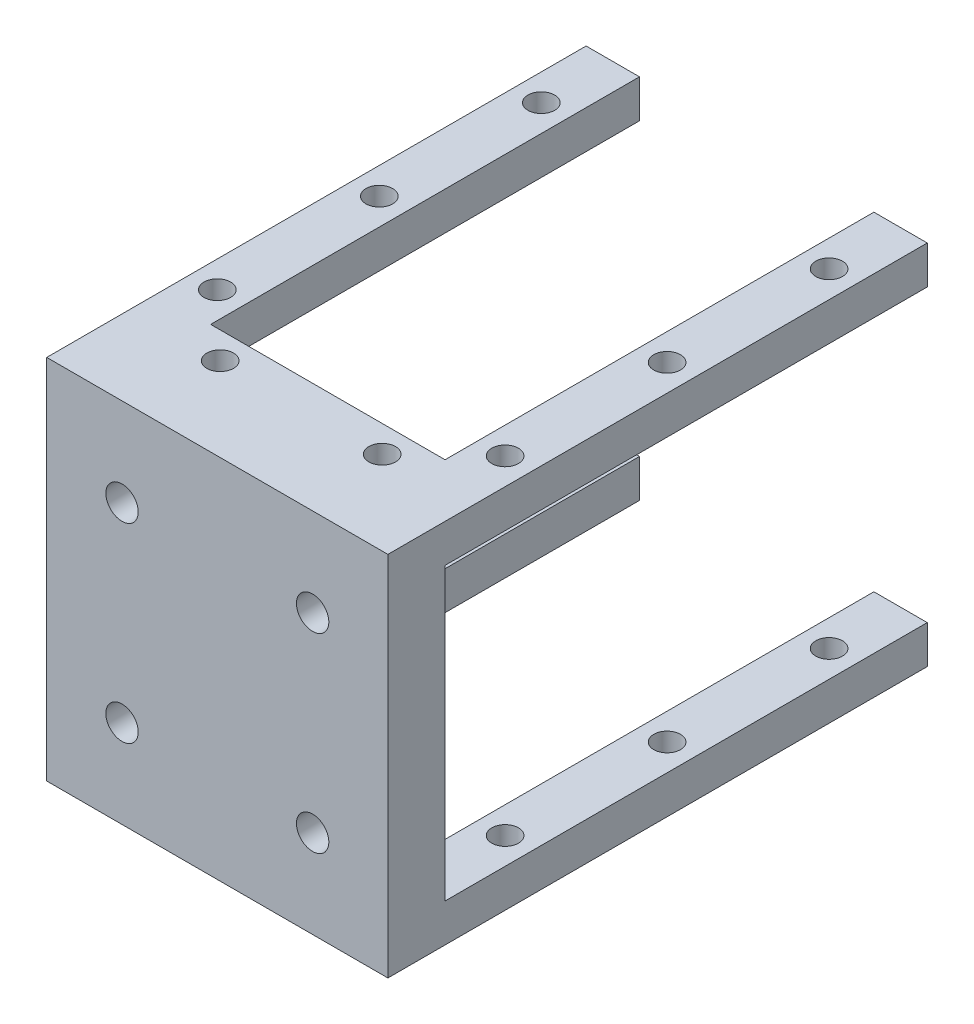
SolidWorks part; units mm, degrees
ref_plane "Front Plane" through (0, 0, 0) normal (0, 0, 1) x (1, 0, 0)
ref_plane "Top Plane" through (0, 0, 0) normal (0, 1, 0) x (1, 0, 0)
ref_plane "Right Plane" through (0, 0, 0) normal (1, 0, 0) x (0, 0, -1)
sketch "Sketch1" plane through (0, 0, 0) normal (0, 1, 0) x (1, 0, 0)
  line L0 (-17.9, 45) -> (-17.9, -5.6)
  line L1 (-17.9, -5.6) -> (17.9, -5.6)
  line L2 (17.9, -5.6) -> (17.9, 45)
  line L3 (17.9, 45) -> (12.3, 45)
  line L4 (12.3, 45) -> (12.3, 0)
  line L5 (12.3, 0) -> (-12.3, 0)
  line L6 (-12.3, 0) -> (-12.3, 45)
  line L7 (-12.3, 45) -> (-17.9, 45)
  line L8 (0, 0) -> (0, -5.6) construction
  line L9 (-17.9, -2.8) -> (17.9, -2.8) construction
  line L10 (15.1, 45) -> (15.1, -5.6) construction
  circle A0 centre (-8.5, -2.8) radius 1.4
  circle A1 centre (8.5, -2.8) radius 1.4
  circle A2 centre (15.1, 37.5) radius 1.4
  circle A3 centre (15.1, 20.5) radius 1.4
  circle A4 centre (15.1, 3.5) radius 1.4
  circle A5 centre (-15.1, 3.5) radius 1.4
  circle A6 centre (-15.1, 20.5) radius 1.4
  circle A7 centre (-15.1, 37.5) radius 1.4
  point P4 (0, 0)
  point P19 (0, -2.8)
  point P22 (0, -5.6)
  dimension "D5" = 2.8
  dimension "D6" = 17
  dimension "D7" = 2.8
  dimension "D9" = 24.5
  dimension "D1" = 5.6
  dimension "D2" = 24.6
  dimension "D3" = 5.6
  dimension "D4" = 50.6
  dimension "D8" = 3
extrude "Boss-Extrude1" add sketch "Sketch1" along normal blind 4
ref_plane "Plane1" through (0, 34.5, 0) normal (0, 1, 0) x (1, 0, 0)
sketch "Sketch2" plane through (0, 34.5, 0) normal (0, 1, 0) x (1, 0, 0)
  line L0 (-17.9, -5.6) -> (17.9, -5.6) construction
  line L1 (12.3, 0) -> (-12.3, 0) construction
  line L2 (17.9, -5.6) -> (17.9, 45) construction
  line L3 (17.9, 45) -> (12.3, 45) construction
  line L4 (12.3, 45) -> (12.3, 0) construction
  line L5 (-12.3, 0) -> (-12.3, 45) construction
  line L6 (-17.9, 45) -> (-17.9, -5.6) construction
  line L7 (-12.3, 45) -> (-17.9, 45) construction
  line L8 (-17.9, -5.6) -> (17.9, -5.6)
  line L9 (12.3, 0) -> (-12.3, 0)
  line L10 (17.9, -5.6) -> (17.9, 45)
  line L11 (17.9, 45) -> (12.3, 45)
  line L12 (12.3, 45) -> (12.3, 0)
  line L13 (-12.3, 0) -> (-12.3, 45)
  line L14 (-17.9, 45) -> (-17.9, -5.6)
  line L15 (-12.3, 45) -> (-17.9, 45)
  circle A0 centre (8.5, -2.8) radius 1.4 construction
  circle A1 centre (-8.5, -2.8) radius 1.4 construction
  circle A2 centre (-15.1, 3.5) radius 1.4 construction
  circle A3 centre (-15.1, 20.5) radius 1.4 construction
  circle A4 centre (15.1, 3.5) radius 1.4 construction
  circle A5 centre (15.1, 20.5) radius 1.4 construction
  circle A6 centre (15.1, 37.5) radius 1.4 construction
  circle A7 centre (-15.1, 37.5) radius 1.4 construction
  circle A8 centre (8.5, -2.8) radius 1.4
  circle A9 centre (-8.5, -2.8) radius 1.4
  circle A10 centre (-15.1, 3.5) radius 1.4
  circle A11 centre (-15.1, 20.5) radius 1.4
  circle A12 centre (15.1, 3.5) radius 1.4
  circle A13 centre (15.1, 20.5) radius 1.4
  circle A14 centre (15.1, 37.5) radius 1.4
  circle A15 centre (-15.1, 37.5) radius 1.4
extrude "Boss-Extrude2" add sketch "Sketch2" along normal blind 4 separate body
sketch "Sketch3" plane through (0, 0, 5.6) normal (0, 0, 1) x (1, 0, 0)
  line L1 (-17.9, 38.5) -> (17.9, 38.5)
  line L2 (-17.9, 38.5) -> (-17.9, 0)
  line L3 (-17.9, 0) -> (17.9, 0)
  line L4 (17.9, 38.5) -> (17.9, 0)
  line L5 (0, 0) -> (0, 38.5) construction
  line L6 (-17.9, 19.25) -> (17.9, 19.25) construction
  point P420 (0, 19.25)
extrude "Boss-Extrude3" add sketch "Sketch3" along normal blind 6
sketch "Sketch4" plane through (0, 0, 5.6) normal (0, 0, -1) x (-1, 0, 0)
  line L0 (-12.3, 34.5) -> (12.3, 34.5) construction
  line L1 (-10, 29.25) -> (10, 29.25) construction
  line L2 (-10, 29.25) -> (-10, 9.25) construction
  line L3 (-10, 9.25) -> (10, 9.25) construction
  line L4 (10, 29.25) -> (10, 9.25) construction
  line L5 (0, 9.25) -> (0, 29.25) construction
  line L6 (-10, 19.25) -> (10, 19.25) construction
  line L7 (-17.9, 4) -> (-17.9, 34.5) construction
  line L8 (8.3257, 26.35) -> (6.6514, 29.25)
  line L9 (-8.3257, 26.35) -> (-6.6514, 29.25)
  line L10 (-6.6514, 29.25) -> (-8.3257, 32.15)
  line L11 (-8.3257, 32.15) -> (-11.6743, 32.15)
  line L12 (-11.6743, 32.15) -> (-13.3486, 29.25)
  line L13 (-13.3486, 29.25) -> (-11.6743, 26.35)
  line L14 (-11.6743, 26.35) -> (-8.3257, 26.35)
  line L15 (11.6743, 26.35) -> (8.3257, 26.35)
  line L16 (13.3486, 29.25) -> (11.6743, 26.35)
  line L17 (11.6743, 32.15) -> (13.3486, 29.25)
  line L18 (8.3257, 32.15) -> (11.6743, 32.15)
  line L19 (6.6514, 29.25) -> (8.3257, 32.15)
  line L20 (6.6514, 9.25) -> (8.3257, 6.35)
  line L21 (8.3257, 6.35) -> (11.6743, 6.35)
  line L22 (11.6743, 6.35) -> (13.3486, 9.25)
  line L23 (13.3486, 9.25) -> (11.6743, 12.15)
  line L24 (11.6743, 12.15) -> (8.3257, 12.15)
  line L25 (8.3257, 12.15) -> (6.6514, 9.25)
  line L26 (-6.6514, 9.25) -> (-8.3257, 6.35)
  line L27 (-8.3257, 6.35) -> (-11.6743, 6.35)
  line L28 (-11.6743, 6.35) -> (-13.3486, 9.25)
  line L29 (-13.3486, 9.25) -> (-11.6743, 12.15)
  line L30 (-11.6743, 12.15) -> (-8.3257, 12.15)
  line L31 (-8.3257, 12.15) -> (-6.6514, 9.25)
  circle A0 centre (-10, 29.25) radius 2.9 construction
  point P4 (0, 0)
  point P7 (0, 34.5)
  point P11 (-17.9, 19.25)
  point P404 (0, 19.25)
  dimension "D1" = 20
  dimension "D2" = 20
  dimension "D3" = 5.8
extrude "Cut-Extrude1" cut sketch "Sketch4" against normal blind 3.5
sketch "Sketch5" plane through (0, 0, 5.6) normal (0, 0, -1) x (-1, 0, 0)
  line L0 (-10, 9.25) -> (10, 9.25) construction
  line L1 (10, 29.25) -> (10, 9.25) construction
  line L2 (-10, 29.25) -> (10, 29.25) construction
  line L3 (-10, 29.25) -> (-10, 9.25) construction
  line L4 (-10, 9.25) -> (10, 9.25) construction
  line L5 (10, 29.25) -> (10, 9.25) construction
  line L6 (-10, 29.25) -> (10, 29.25) construction
  line L7 (-10, 29.25) -> (-10, 9.25) construction
  circle A0 centre (-10, 29.25) radius 1.7
  circle A1 centre (-10, 9.25) radius 1.7
  circle A2 centre (10, 9.25) radius 1.7
  circle A3 centre (10, 29.25) radius 1.7
  point P7 (-10, 8.9383)
  point P9 (9.6783, 9.25)
  point P11 (10, 28.9029)
  dimension "D1" = 3.4
extrude "Cut-Extrude3" cut sketch "Sketch5" against normal through all
